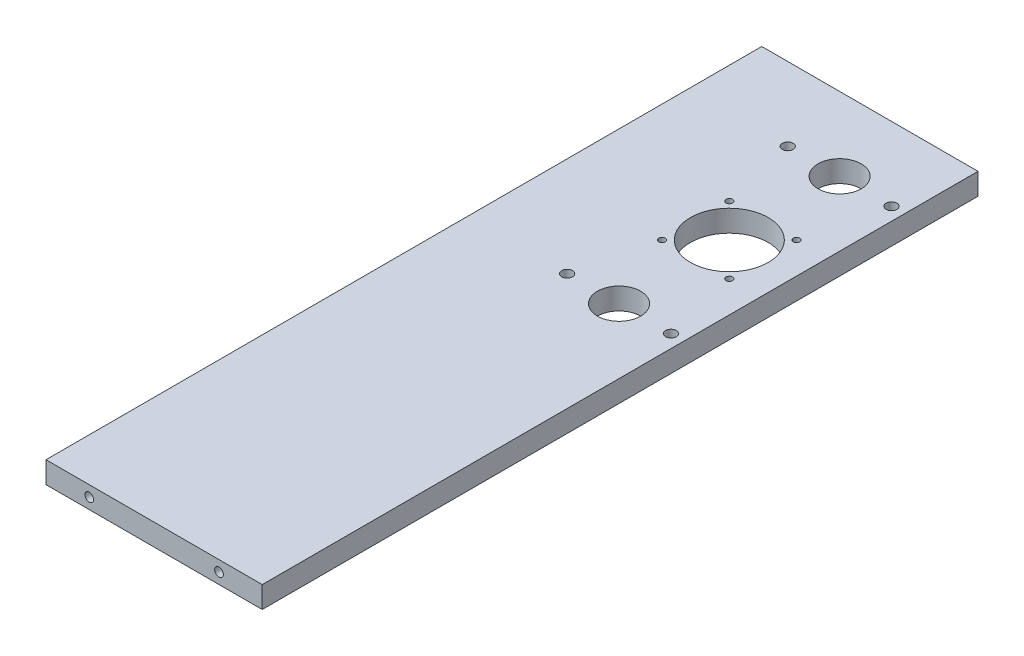
SolidWorks part; units mm, degrees
ref_plane "Front Plane" through (0, 0, 0) normal (0, 0, 1) x (1, 0, 0)
ref_plane "Top Plane" through (0, 0, 0) normal (0, 1, 0) x (1, 0, 0)
ref_plane "Right Plane" through (0, 0, 0) normal (1, 0, 0) x (0, 0, -1)
sketch "Sketch1" plane through (0, 0, 0) normal (0, 1, 0) x (1, 0, 0)
  line L0 (20.7761, 31.1641) -> (20.7761, -299.8359)
  line L1 (20.7761, -299.8359) -> (-79.2239, -299.8359)
  line L2 (-79.2239, -299.8359) -> (-79.2239, 31.1641)
  line L3 (-79.2239, 31.1641) -> (20.7761, 31.1641)
  dimension "D1" = 331
  dimension "D3" = 100
extrude "Boss-Extrude1" add sketch "Sketch1" along normal blind 10
sketch "Sketch2" plane through (0, 10, 0) normal (0, 1, 0) x (1, 0, 0)
  line L0 (20.7761, -299.8359) -> (20.7761, 31.1641) construction
  line L2 (-33.2239, -2.8359) -> (-9.2239, -2.8359) construction
  line L3 (-9.2239, -2.8359) -> (14.7761, -2.8359) construction
  line L4 (-33.2239, -104.8359) -> (-9.2239, -104.8359) construction
  line L5 (-9.2239, -104.8359) -> (14.7761, -104.8359) construction
  line L6 (-9.2239, -2.8359) -> (-9.2239, -53.8359) construction
  line L7 (-9.2239, -53.8359) -> (-9.2239, -104.8359) construction
  line L9 (-24.7803, -69.3922) -> (6.3324, -69.3922) construction
  line L10 (6.3324, -69.3922) -> (6.3324, -38.2796) construction
  line L11 (6.3324, -38.2796) -> (-24.7803, -38.2796) construction
  line L12 (-24.7803, -38.2796) -> (-24.7803, -69.3922) construction
  circle A0 centre (-9.2239, -2.8359) radius 10
  circle A1 centre (-33.2239, -2.8359) radius 2.5
  circle A2 centre (14.7761, -2.8359) radius 2.5
  circle A3 centre (-9.2239, -104.8359) radius 10
  circle A4 centre (-33.2239, -104.8359) radius 2.5
  circle A5 centre (14.7761, -104.8359) radius 2.5
  circle A6 centre (-9.2239, -53.8359) radius 18
  circle A7 centre (-9.2239, -53.8359) radius 15.5563 construction
  circle A8 centre (6.3324, -38.2796) radius 1.5
  circle A9 centre (6.3324, -69.3922) radius 1.5
  circle A10 centre (-24.7803, -69.3922) radius 1.5
  circle A11 centre (-24.7803, -38.2796) radius 1.5
  dimension "D3" = 20
  dimension "D4" = 5
  dimension "D8" = 36
  dimension "D10" = 3
  dimension "D1" = 30
  dimension "D2" = 195
  dimension "D5" = 24
  dimension "D7" = 102
  dimension "D9" = 44
  dimension "D6" = 2
extrude "Cut-Extrude1" cut sketch "Sketch2" against normal through all
sketch "Sketch3" plane through (0, 0, 299.8359) normal (0, 0, 1) x (1, 0, 0)
  line L0 (-79.2239, 0) -> (20.7761, 0) construction
  line L3 (-29.2239, 5) -> (-59.2239, 5) construction
  line L4 (-29.2239, 5) -> (0.7761, 5) construction
  circle A0 centre (-59.2239, 5) radius 2
  circle A1 centre (0.7761, 5) radius 2
  point P2 (-29.2239, 0)
  dimension "D2" = 4
  dimension "D1" = 30
extrude "Cut-Extrude2" cut sketch "Sketch3" against normal blind 15
